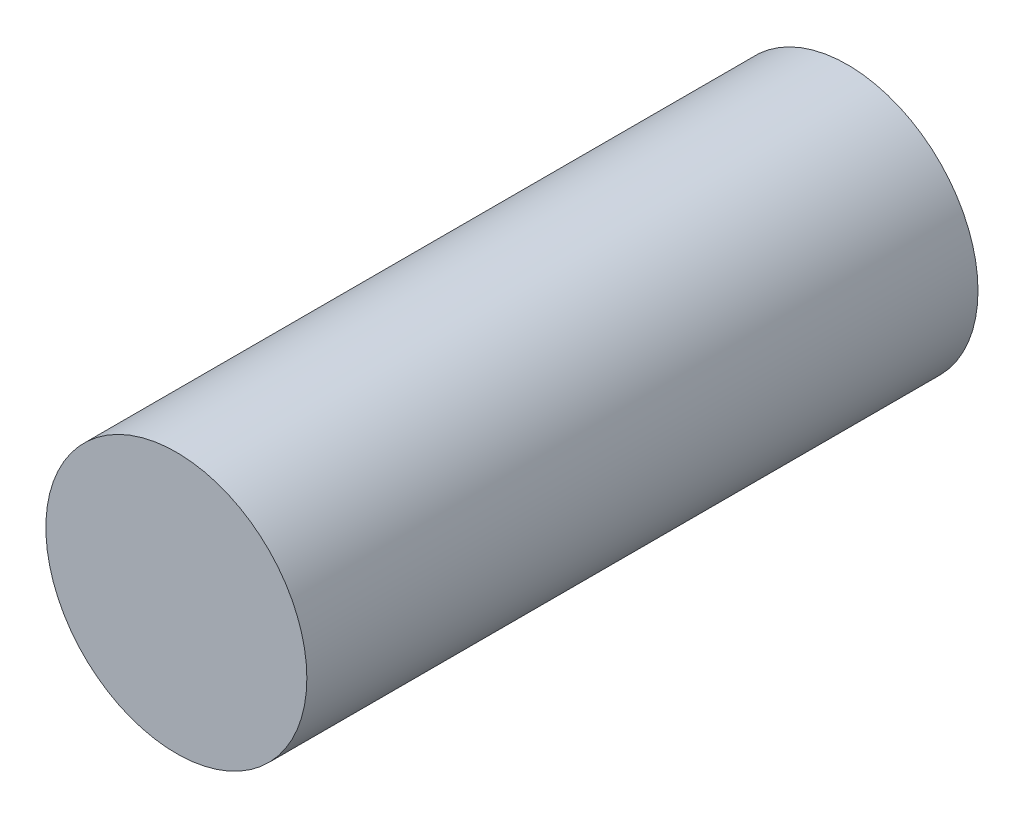
SolidWorks part; units mm, degrees
ref_plane "Front Plane" through (0, 0, 0) normal (0, 0, 1) x (1, 0, 0)
ref_plane "Top Plane" through (0, 0, 0) normal (0, 1, 0) x (1, 0, 0)
ref_plane "Right Plane" through (0, 0, 0) normal (1, 0, 0) x (0, 0, -1)
sketch "Sketch1" plane through (0, 0, 0) normal (0, 0, 1) x (1, 0, 0)
  circle A0 centre (0, 0) radius 7
  dimension "D1" = 14
extrude "Boss-Extrude1" add sketch "Sketch1" along normal blind 36
